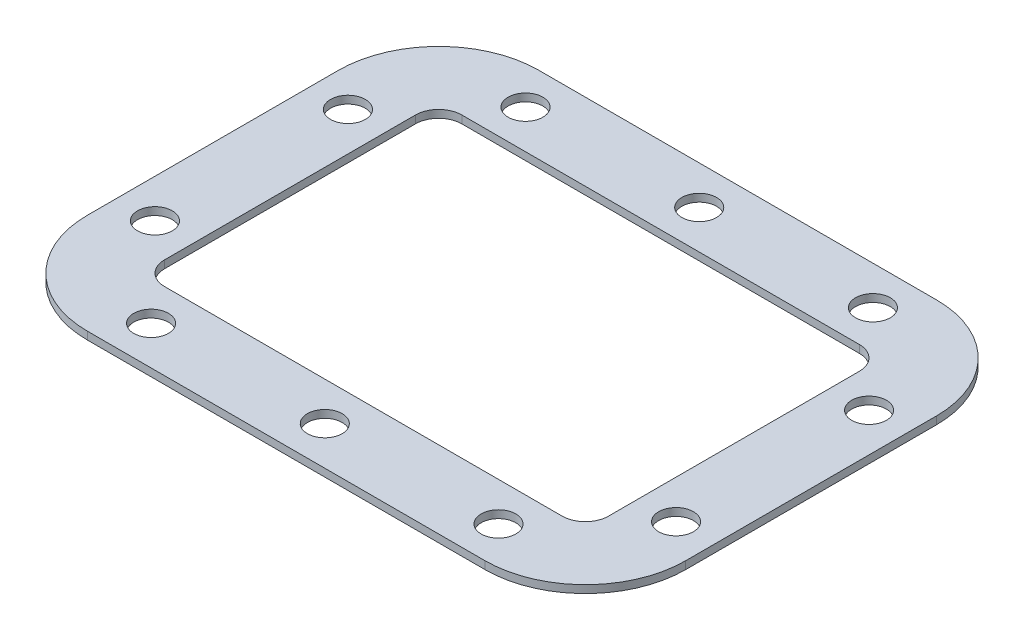
SolidWorks part; units mm, degrees
material "Резина"
ref_plane "Спереди" through (0, 0, 0) normal (0, 0, 1) x (1, 0, 0)
ref_plane "Сверху" through (0, 0, 0) normal (0, 1, 0) x (1, 0, 0)
ref_plane "Справа" through (0, 0, 0) normal (1, 0, 0) x (0, 0, -1)
sketch "Эскиз2" plane through (0, 0, 0) normal (0, 1, 0) x (1, 0, 0)
  line L0 (-51.5, 38.5) -> (51.5, 38.5)
  line L1 (-51.5, -58.5) -> (51.5, -58.5)
  line L2 (-77.5, -32.5) -> (-77.5, 32.5)
  line L3 (-51.5, 58.5) -> (51.5, 58.5)
  line L4 (77.5, -32.5) -> (77.5, 32.5)
  line L5 (-77.5, -58.5) -> (77.5, 58.5) construction
  line L6 (-77.5, 58.5) -> (77.5, -58.5) construction
  line L7 (57.5, -32.5) -> (57.5, 32.5)
  line L8 (-51.5, -38.5) -> (51.5, -38.5)
  line L9 (-57.5, -32.5) -> (-57.5, 32.5)
  arc A0 (51.5, -58.5) -> (77.5, -32.5) centre (51.5, -32.5) ccw
  arc A1 (51.5, 58.5) -> (77.5, 32.5) centre (51.5, 32.5) cw
  arc A2 (-77.5, 32.5) -> (-51.5, 58.5) centre (-51.5, 32.5) cw
  arc A3 (-51.5, -58.5) -> (-77.5, -32.5) centre (-51.5, -32.5) cw
  arc A4 (51.5, 38.5) -> (57.5, 32.5) centre (51.5, 32.5) cw
  arc A5 (51.5, -38.5) -> (57.5, -32.5) centre (51.5, -32.5) ccw
  arc A6 (-51.5, -38.5) -> (-57.5, -32.5) centre (-51.5, -32.5) cw
  arc A7 (-57.5, 32.5) -> (-51.5, 38.5) centre (-51.5, 32.5) cw
  point P0 (0, 0)
  dimension "D3" = 26
  dimension "D1" = 117
  dimension "D2" = 155
  dimension "D4" = 20
extrude "Бобышка-Вытянуть1" add sketch "Эскиз2" along normal blind 2
sketch "Эскиз4" plane through (0, 2, 0) normal (0, 1, 0) x (1, 0, 0)
  line L0 (-94.2995, 0) -> (93.0823, 0) construction
  line L1 (0, 67.0075) -> (0, -71.5241) construction
  circle A0 centre (-45, -48.5) radius 4.5
  dimension "D1" = 9
  dimension "D3" = 90
  dimension "D2" = 97
extrude "Вырез-Вытянуть1" cut sketch "Эскиз4" against normal through all
sketch "Эскиз6" plane through (0, 2, 0) normal (0, 1, 0) x (1, 0, 0)
  line L0 (-89.2461, 0) -> (88.9647, 0) construction
  line L1 (0, 65.366) -> (0, -73.0253) construction
  point P0 (0, -48.5)
  point P1 (45, -48.5)
  point P2 (67.5, -25)
  point P3 (67.5, 25)
  point P14 (-67.5, -25)
  point P15 (-67.5, 25)
  point P16 (45, 48.5)
  point P17 (0, 48.5)
  point P18 (-45, 48.5)
  dimension "D1" = 135
  dimension "D2" = 50
pattern_sketch "Эскиз-Массив1" of "Вырез-Вытянуть1" driven by "Эскиз6"
